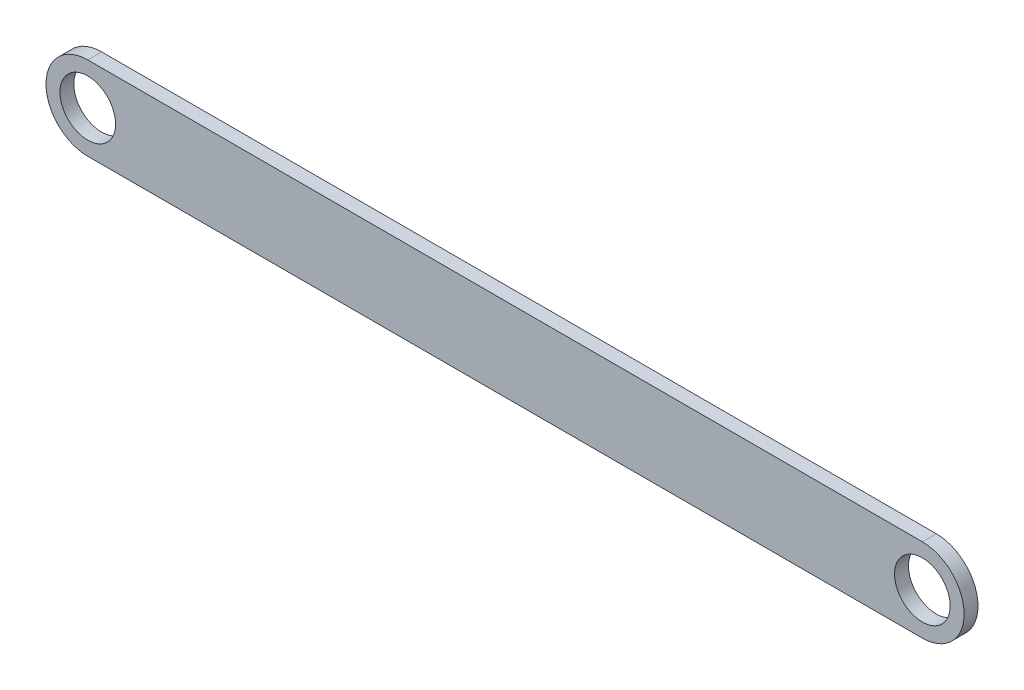
SolidWorks part; units mm, degrees
ref_plane "Front Plane" through (0, 0, 0) normal (0, 0, 1) x (1, 0, 0)
ref_plane "Top Plane" through (0, 0, 0) normal (0, 1, 0) x (1, 0, 0)
ref_plane "Right Plane" through (0, 0, 0) normal (1, 0, 0) x (0, 0, -1)
sketch "Sketch1" plane through (0, 0, 0) normal (0, 0, 1) x (1, 0, 0)
  line L0 (0, 0) -> (3000, 0) construction
  line L1 (0, 150) -> (3000, 150)
  line L2 (0, -150) -> (3000, -150)
  circle A0 centre (0, 0) radius 100
  circle A1 centre (3000, 0) radius 100
  arc A2 (0, 150) -> (0, -150) centre (0, 0) ccw
  arc A3 (3000, -150) -> (3000, 150) centre (3000, 0) ccw
  point P5 (1500, 0)
  dimension "D1" = 200
  dimension "D2" = 200
  dimension "D4" = 150
  dimension "D3" = 3000
extrude "Boss-Extrude1" add sketch "Sketch1" along normal blind 50
